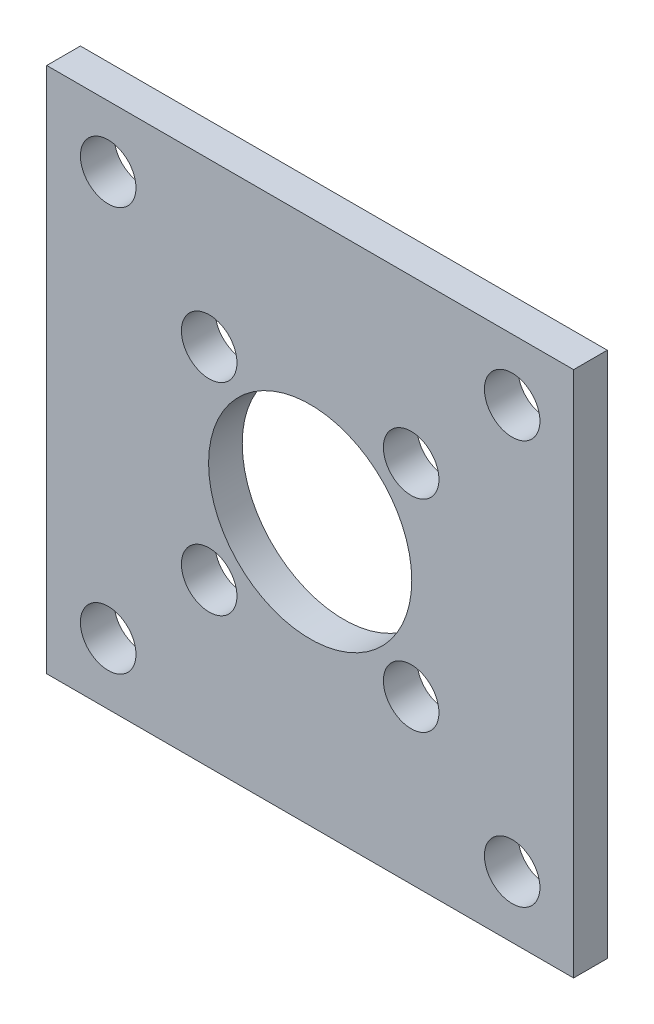
SolidWorks part; units mm, degrees
material "Acrylic (Medium-high impact)"
ref_plane "Front Plane" through (0, 0, 0) normal (0, 0, 1) x (1, 0, 0)
ref_plane "Top Plane" through (0, 0, 0) normal (0, 1, 0) x (1, 0, 0)
ref_plane "Right Plane" through (0, 0, 0) normal (1, 0, 0) x (0, 0, -1)
sketch "Sketch1" plane through (0, 0, 0) normal (0, 0, 1) x (1, 0, 0)
  line L0 (69.125, 69.125) -> (9.125, 9.125) construction
  line L1 (0, 0) -> (78.25, 0)
  line L2 (0, 0) -> (0, 78.25)
  line L3 (0, 78.25) -> (78.25, 78.25)
  line L4 (78.25, 0) -> (78.25, 78.25)
  line L5 (9.125, 9.125) -> (69.125, 9.125) construction
  line L6 (9.125, 9.125) -> (9.125, 69.125) construction
  line L7 (9.125, 69.125) -> (69.125, 69.125) construction
  line L8 (69.125, 9.125) -> (69.125, 69.125) construction
  line L9 (5, 9.125) -> (0, 9.125) construction
  line L10 (64.8959, 1.8) -> (60.6668, 9.125)
  line L11 (17.5832, 9.125) -> (13.3541, 16.45)
  line L12 (13.3541, 16.45) -> (4.8959, 16.45)
  line L13 (4.8959, 16.45) -> (0.6668, 9.125)
  line L14 (0.6668, 9.125) -> (4.8959, 1.8)
  line L15 (4.8959, 1.8) -> (13.3541, 1.8)
  line L16 (13.3541, 1.8) -> (17.5832, 9.125)
  line L17 (73.3541, 1.8) -> (64.8959, 1.8)
  line L18 (77.5832, 9.125) -> (73.3541, 1.8)
  line L19 (73.3541, 16.45) -> (77.5832, 9.125)
  line L20 (9.125, 39.125) -> (0, 39.125) construction
  line L21 (39.125, 9.125) -> (39.125, 0) construction
  line L22 (64.8959, 16.45) -> (73.3541, 16.45)
  line L23 (60.6668, 9.125) -> (64.8959, 16.45)
  line L24 (73.3541, 61.8) -> (77.5832, 69.125)
  line L25 (77.5832, 69.125) -> (73.3541, 76.45)
  line L26 (73.3541, 76.45) -> (64.8959, 76.45)
  line L27 (64.8959, 76.45) -> (60.6668, 69.125)
  line L28 (60.6668, 69.125) -> (64.8959, 61.8)
  line L29 (64.8959, 61.8) -> (73.3541, 61.8)
  line L30 (4.8959, 61.8) -> (0.6668, 69.125)
  line L31 (0.6668, 69.125) -> (4.8959, 76.45)
  line L32 (4.8959, 76.45) -> (13.3541, 76.45)
  line L33 (13.3541, 76.45) -> (17.5832, 69.125)
  line L34 (17.5832, 69.125) -> (13.3541, 61.8)
  line L35 (13.3541, 61.8) -> (4.8959, 61.8)
  line L36 (39.125, 9.125) -> (39.125, 24.125) construction
  line L37 (24.125, 54.125) -> (54.125, 54.125) construction
  line L38 (24.125, 54.125) -> (24.125, 24.125) construction
  line L39 (24.125, 24.125) -> (54.125, 24.125) construction
  line L40 (54.125, 54.125) -> (54.125, 24.125) construction
  line L41 (24.125, 39.125) -> (9.125, 39.125) construction
  circle A0 centre (9.125, 9.125) radius 4.125
  circle A1 centre (9.125, 9.125) radius 7.325 construction
  circle A2 centre (69.125, 9.125) radius 4.125
  circle A3 centre (69.125, 69.125) radius 4.125
  circle A4 centre (39.125, 39.125) radius 15.0882
  circle A5 centre (9.125, 69.125) radius 4.125
  circle A6 centre (24.125, 24.125) radius 4.125
  circle A7 centre (54.125, 24.125) radius 4.125
  circle A8 centre (24.125, 54.125) radius 4.125
  circle A9 centre (54.125, 54.125) radius 4.125
  point P47 (39.125, 69.125)
  point P48 (49.794, 49.794)
  point P58 (51.2082, 51.2082)
  dimension "D2" = 8.25
  dimension "D3" = 5
  dimension "D4" = 2
  dimension "D1" = 60
  dimension "D5" = 14.65
  dimension "D6" = 30
extrude "Boss-Extrude1" add sketch "Sketch1" along normal blind 5 contours L1 L4 L3 L2 A4 L10 L23 L22 L19 L18 L17 L16 L15 L14 L13 L12 L11 L29 L28 L27 L26 L25 L24 L34 L35 L30 L31 L32 L33 | L35 L34 L33 L32 L31 L30 A5 | L15 L16 L11 L12 L13 L14 A0 | L23 L10 L17 L18 L19 L22 A2 | L28 L29 L24 L25 L26 L27 A3
